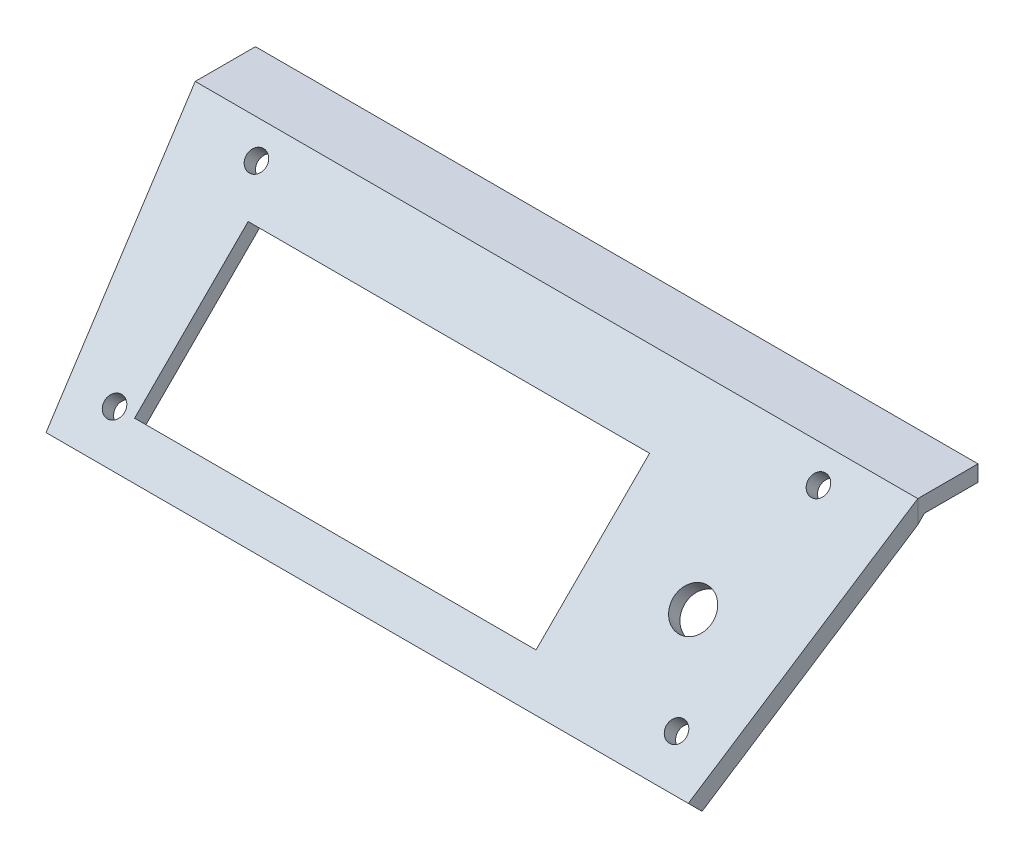
SolidWorks part; units mm, degrees
ref_plane "前基準面" through (0, 0, 0) normal (0, 0, 1) x (1, 0, 0)
ref_plane "上基準面" through (0, 0, 0) normal (0, 1, 0) x (1, 0, 0)
ref_plane "右基準面" through (0, 0, 0) normal (1, 0, 0) x (0, 0, -1)
sketch "草圖1" plane through (0, 0, 0) normal (1, 0, 0) x (0, 0, -1)
  line L0 (-59.3431, 0) -> (-13.3431, 46)
  line L1 (-13.3431, 46) -> (0, 46)
  line L2 (0, 46) -> (0, 50)
  line L3 (0, 50) -> (-15, 50)
  line L4 (-15, 50) -> (-62.1716, 2.8284)
  line L5 (-62.1716, 2.8284) -> (-59.3431, 0)
  dimension "D1" = 50
  dimension "D2" = 4
  dimension "D3" = 4
  dimension "D4" = 15
  dimension "D5" = 135
extrude "填料-伸長1" add sketch "草圖1" along normal mid plane 180
sketch "草圖3" plane through (0, 0, 0) normal (0, 1, 0) x (1, 0, 0)
  line L0 (-90, -15) -> (-90, -62.1716)
  line L1 (-90, -62.1716) -> (-80, -62.1716)
  line L2 (90, -62.1716) -> (-90, -62.1716) construction
  line L3 (-80, -62.1716) -> (-90, -15)
  line L4 (90, -15) -> (80, -62.1716)
  line L5 (80, -62.1716) -> (90, -62.1716)
  line L6 (90, -62.1716) -> (90, -15)
  line L7 (-80, -62.1716) -> (80, -62.1716) construction
  line L8 (0, 0) -> (0, -62.1716) construction
  dimension "D1" = 160
extrude "除料-伸長1" cut sketch "草圖3" along normal blind 160
sketch "草圖4" plane through (0, 32.5, 32.5) normal (0, 0.7071, 0.7071) x (1, 0, 0)
  line L0 (80, -41.9619) -> (-80, -41.9619) construction
  line L1 (35, -31.9619) -> (-65, -31.9619)
  line L2 (35, -31.9619) -> (35, 8.0381)
  line L3 (35, 8.0381) -> (-65, 8.0381)
  line L4 (-65, -31.9619) -> (-65, 8.0381)
  dimension "D1" = 40
  dimension "D2" = 100
  dimension "D3" = 10
  dimension "D4" = 15
extrude "除料-伸長2" cut sketch "草圖4" against normal through all
sketch "草圖5" plane through (0, 32.5, 32.5) normal (0, 0.7071, 0.7071) x (1, 0, 0)
  line L0 (35, -31.9619) -> (35, 8.0381) construction
  line L1 (35, -11.9619) -> (60, -11.9619) construction
  circle A0 centre (60, -11.9619) radius 5
  dimension "D1" = 10
  dimension "D2" = 25
extrude "除料-伸長3" cut sketch "草圖5" against normal through all
sketch "草圖6" plane through (0, 32.5, 32.5) normal (0, 0.7071, 0.7071) x (1, 0, 0)
  line L1 (70, -31.9619) -> (70, 18.0381) construction
  circle A0 centre (70, -31.9619) radius 2.5
  circle A1 centre (70, 18.0381) radius 2.5
  dimension "D1" = 50
  dimension "D3" = 5
  dimension "D4" = 5
  dimension "D2" = 70
extrude "除料-伸長4" cut sketch "草圖6" against normal through all
mirror "鏡射1" about plane through (0, 0, 0) normal (1, 0, 0) of "除料-伸長4"
